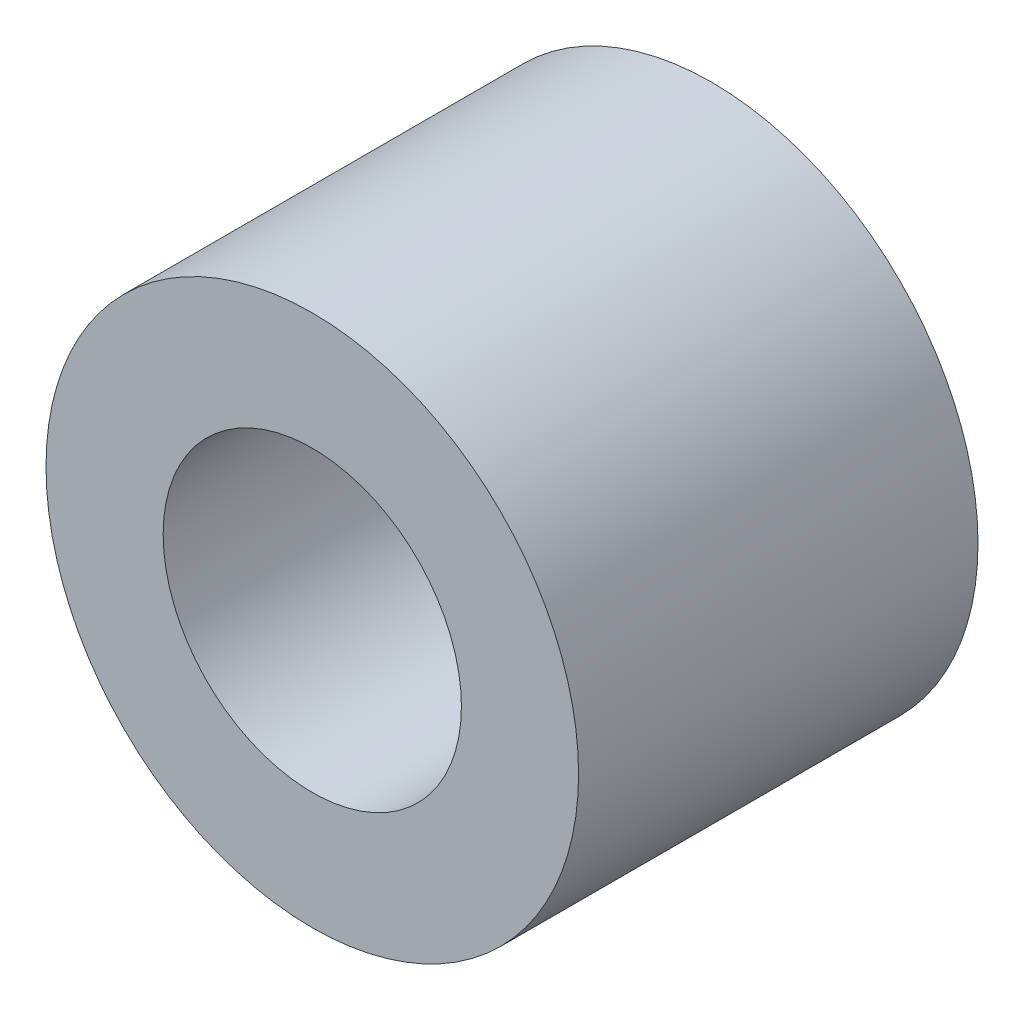
SolidWorks part; units mm, degrees
ref_plane "Front Plane" through (0, 0, 0) normal (0, 0, 1) x (1, 0, 0)
ref_plane "Top Plane" through (0, 0, 0) normal (0, 1, 0) x (1, 0, 0)
ref_plane "Right Plane" through (0, 0, 0) normal (1, 0, 0) x (0, 0, -1)
sketch "Sketch1" plane through (0, 0, 0) normal (0, 0, 1) x (1, 0, 0)
  circle A0 centre (0, 0) radius 3.175
  circle A1 centre (0, 0) radius 1.778
  dimension "OD" = 6.35
  dimension "ID" = 3.556
extrude "Extrude1" add sketch "Sketch1" along normal mid plane 4.7625
sketch "Sketch2" plane through (0, 0, 0) normal (1, 0, 0) x (0, 0, -1)
  line L0 (-2.3813, -1.778) -> (2.3812, -1.778) construction
  line L3 (2.3812, 1.778) -> (-2.3813, 1.778) construction
  line L5 (-2.3813, -1.778) -> (2.3812, -1.778)
  line L6 (2.3812, 1.778) -> (-2.3813, 1.778)
sketch "Sketch4" plane through (0, 0, 2.3813) normal (0, 0, 1) x (1, 0, 0)
  line L0 (0, 0) -> (-1.2572, 1.2572)
  line L1 (0, -2.6194) -> (0, 2.6194) construction
  circle A0 centre (0, 0) radius 1.778 construction
  dimension "D1" = 45
